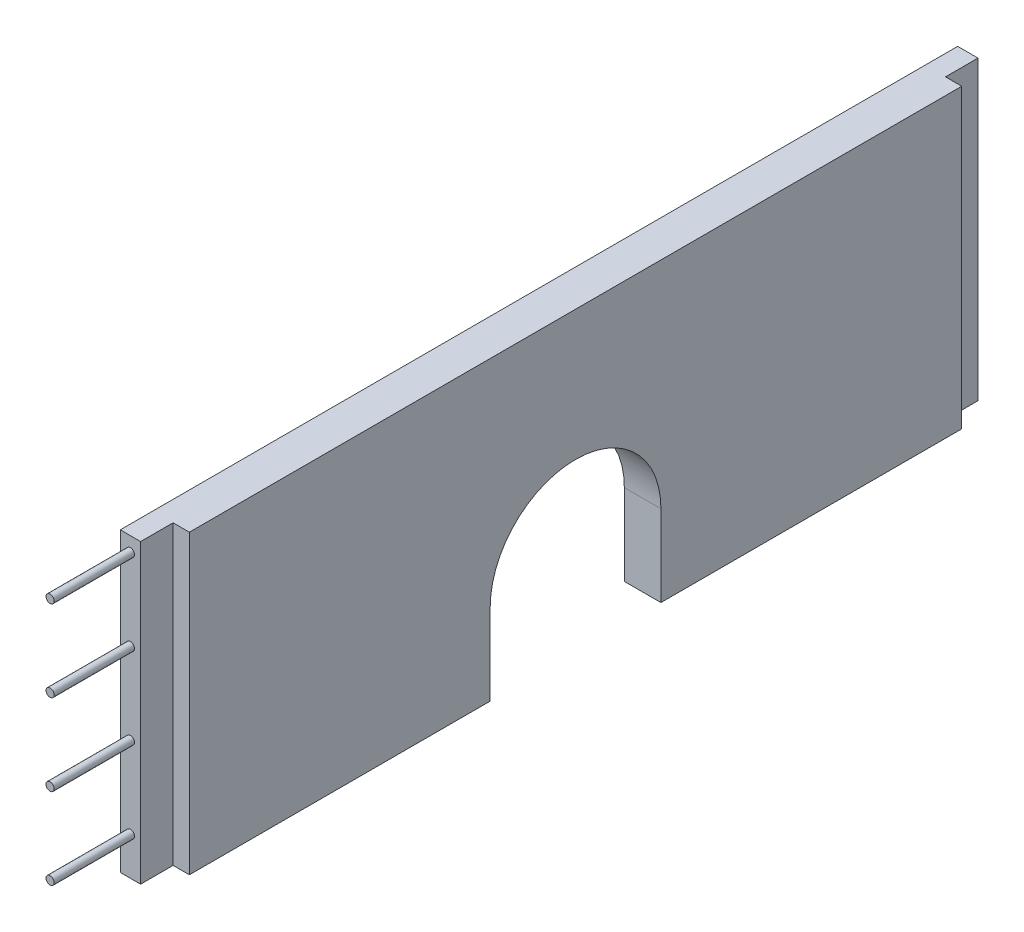
SolidWorks part; units mm, degrees
ref_plane "정면" through (0, 0, 0) normal (0, 0, 1) x (1, 0, 0)
ref_plane "윗면" through (0, 0, 0) normal (0, 1, 0) x (1, 0, 0)
ref_plane "우측면" through (0, 0, 0) normal (1, 0, 0) x (0, 0, -1)
sketch "스케치1" plane through (0, 0, 0) normal (0, 1, 0) x (1, 0, 0)
  line L1 (0, 0) -> (2.5, 0)
  line L2 (0, 0) -> (0, -103)
  line L3 (0, -103) -> (2.5, -103)
  line L4 (2.5, 0) -> (2.5, -103)
  line L5 (2.5, -4) -> (4.5, -4)
  line L6 (2.5, -4) -> (2.5, -99)
  line L7 (2.5, -99) -> (4.5, -99)
  line L8 (4.5, -4) -> (4.5, -99)
  dimension "D1" = 103
  dimension "D2" = 2.5
  dimension "D3" = 95
  dimension "D4" = 4
extrude "보스-돌출1" add sketch "스케치1" along normal blind 99.5 contours L4 L1 L2 L3 | L8 L5 L4 L7
sketch "스케치2" plane through (4.5, 0, 0) normal (1, 0, 0) x (0, 0, -1)
  line L0 (-4, 0) -> (-99, 0) construction
  line L1 (-51.5, 0) -> (-51.5, 17.427) construction
  line L2 (-62, 10) -> (-62, 0)
  line L3 (-41, 10) -> (-41, 0)
  line L4 (-62, 0) -> (-41, 0)
  arc A0 (-41, 10) -> (-62, 10) centre (-51.5, 10) ccw
  dimension "D1" = 21
  dimension "D2" = 10
extrude "컷-돌출2" cut sketch "스케치2" against normal up to surface (4.5 mm away) up to face at (0, 49.75, 51.5)
sketch "스케치3" plane through (0, 99.5, 0) normal (0, 1, 0) x (1, 0, 0)
  line L8 (2.5, -4) -> (2.5, 0)
  line L9 (2.5, 0) -> (0, 0)
  line L10 (0, 0) -> (0, -103)
  line L11 (0, -103) -> (2.5, -103)
  line L12 (2.5, -103) -> (2.5, -99)
  line L13 (2.5, -99) -> (4.5, -99)
  line L14 (4.5, -99) -> (4.5, -4)
  line L15 (4.5, -4) -> (2.5, -4)
  line L16 (2.5, -4) -> (2.5, 0)
  line L17 (2.5, 0) -> (0, 0)
  line L18 (0, 0) -> (0, -103)
  line L19 (0, -103) -> (2.5, -103)
  line L20 (2.5, -103) -> (2.5, -99)
  line L21 (2.5, -99) -> (4.5, -99)
  line L22 (4.5, -99) -> (4.5, -4)
  line L23 (4.5, -4) -> (2.5, -4)
  dimension "D1" = 0
extrude "컷-돌출3" cut sketch "스케치3" against normal blind 58.5
sketch "스케치4" plane through (0, 41, 0) normal (0, 1, 0) x (1, 0, 0)
  line L8 (4.5, -4) -> (2.5, -4)
  line L9 (2.5, -4) -> (2.5, 0)
  line L10 (2.5, 0) -> (0, 0)
  line L11 (0, 0) -> (0, -103)
  line L12 (0, -103) -> (2.5, -103)
  line L13 (2.5, -103) -> (2.5, -99)
  line L14 (2.5, -99) -> (4.5, -99)
  line L15 (4.5, -99) -> (4.5, -4)
  line L16 (4.5, -4) -> (2.5, -4)
  line L17 (2.5, -4) -> (2.5, 0)
  line L18 (2.5, 0) -> (0, 0)
  line L19 (0, 0) -> (0, -103)
  line L20 (0, -103) -> (2.5, -103)
  line L21 (2.5, -103) -> (2.5, -99)
  line L22 (2.5, -99) -> (4.5, -99)
  line L23 (4.5, -99) -> (4.5, -4)
  dimension "D1" = 0
extrude "컷-돌출4" cut sketch "스케치4" against normal blind 4.5
sketch "스케치5" plane through (0, 36.5, 0) normal (0, 1, 0) x (1, 0, 0)
  line L8 (4.5, -99) -> (4.5, -4)
  line L9 (4.5, -4) -> (2.5, -4)
  line L10 (2.5, -4) -> (2.5, 0)
  line L11 (2.5, 0) -> (0, 0)
  line L12 (0, 0) -> (0, -103)
  line L13 (0, -103) -> (2.5, -103)
  line L14 (2.5, -103) -> (2.5, -99)
  line L15 (2.5, -99) -> (4.5, -99)
  line L16 (4.5, -99) -> (4.5, -4)
  line L17 (4.5, -4) -> (2.5, -4)
  line L18 (2.5, -4) -> (2.5, 0)
  line L19 (2.5, 0) -> (0, 0)
  line L20 (0, 0) -> (0, -103)
  line L21 (0, -103) -> (2.5, -103)
  line L22 (2.5, -103) -> (2.5, -99)
  line L23 (2.5, -99) -> (4.5, -99)
  dimension "D1" = 0
sketch "스케치6" plane through (0, 0, 0) normal (0, -1, 0) x (1, 0, 0)
  line L0 (0, 62) -> (0, 103) construction
  line L1 (0, 82.5) -> (1.6, 82.5)
  line L2 (0, 82.5) -> (0, 65.5)
  line L3 (0, 65.5) -> (1.6, 65.5)
  line L4 (1.6, 82.5) -> (1.6, 65.5)
extrude "컷-돌출5" cut sketch "스케치6" against normal blind 10
sketch "스케치7" plane through (0, 0, 103) normal (0, 0, 1) x (1, 0, 0)
  circle A0 centre (1.25, 34.7228) radius 0.5
  circle A1 centre (1.25, 24.7228) radius 0.5
  circle A2 centre (1.25, 14.7228) radius 0.5
  circle A3 centre (1.25, 4.7228) radius 0.5
  dimension "D1" = 1
  dimension "D2" = 4
extrude "보스-돌출2" add sketch "스케치7" along normal up to surface (9.8865 mm away) contours A0 | A1 | A2 | A3
